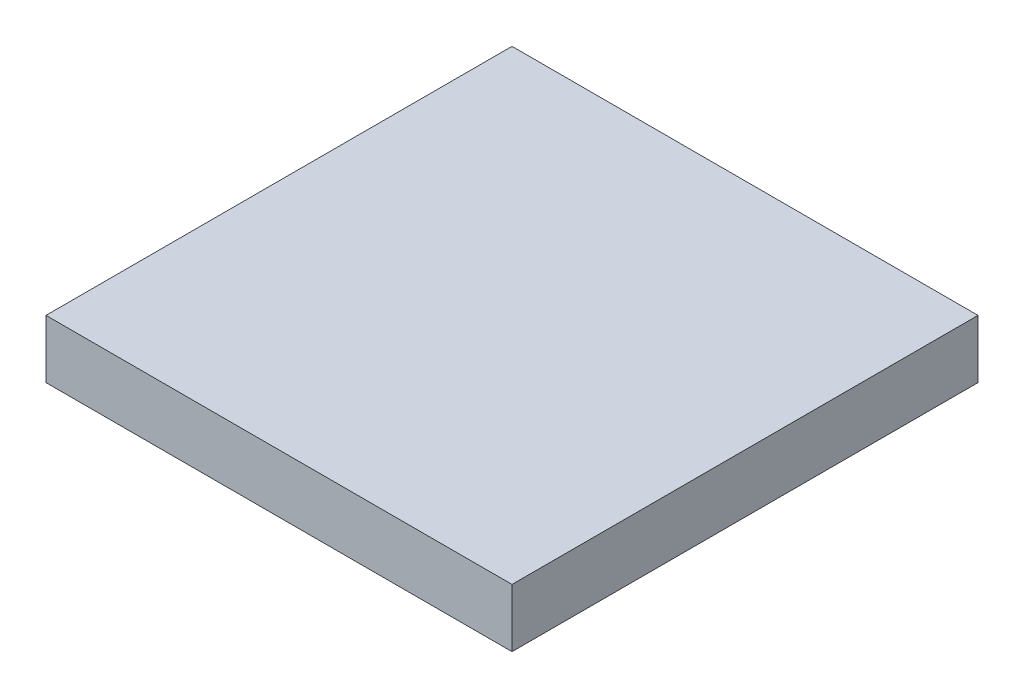
SolidWorks part; units mm, degrees
material "AISI 304"
ref_plane "Front" through (0, 0, 0) normal (0, 0, 1) x (1, 0, 0)
ref_plane "Top" through (0, 0, 0) normal (0, 1, 0) x (1, 0, 0)
ref_plane "Right" through (0, 0, 0) normal (1, 0, 0) x (0, 0, -1)
sketch "Sketch1" plane through (0, 0, 0) normal (0, 1, 0) x (1, 0, 0)
  line L1 (-60, -60) -> (60, -60)
  line L2 (-60, -60) -> (-60, 60)
  line L3 (-60, 60) -> (60, 60)
  line L4 (60, -60) -> (60, 60)
  line L5 (-60, -60) -> (60, 60) construction
  line L6 (-60, 60) -> (60, -60) construction
  point P0 (0, 0)
  dimension "D1" = 120
  dimension "D2" = 120
extrude "Boss-Extrude1" add sketch "Sketch1" along normal mid plane 15
